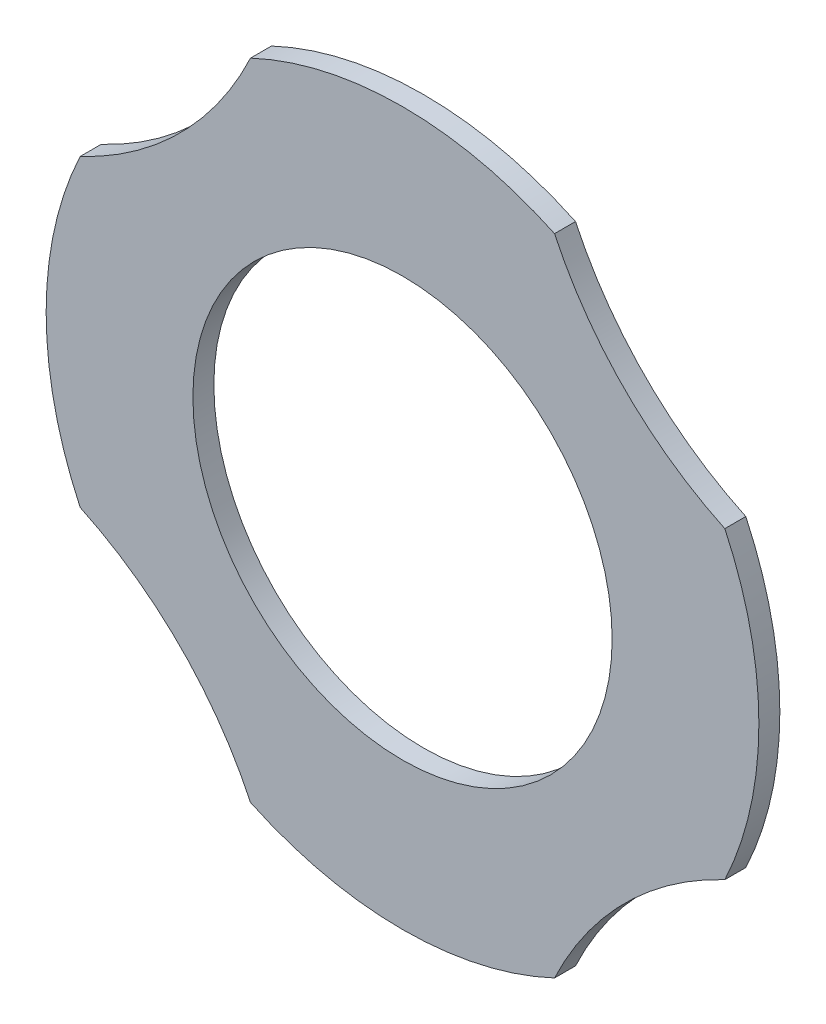
SolidWorks part; units mm, degrees
ref_plane "Alzado" through (0, 0, 0) normal (0, 0, 1) x (1, 0, 0)
ref_plane "Planta" through (0, 0, 0) normal (0, 1, 0) x (1, 0, 0)
ref_plane "Vista lateral" through (0, 0, 0) normal (1, 0, 0) x (0, 0, -1)
sketch "Croquis1" plane through (0, 0, 0) normal (0, 0, 1) x (1, 0, 0)
  line L0 (0, 320) -> (0, 650) construction
  line L1 (0, 320) -> (233.3452, 553.3452) construction
  line L2 (0, 320) -> (330, 320) construction
  line L3 (0, 320) -> (233.3452, 86.6548) construction
  line L4 (0, 320) -> (0, -10) construction
  line L5 (0, 320) -> (-233.3452, 86.6548) construction
  line L6 (0, 320) -> (-330, 320) construction
  line L7 (0, 320) -> (-233.3452, 553.3452) construction
  line L8 (0, 320) -> (0, 650) construction
  line L9 (0, 320) -> (72.5169, 473.7573) construction
  circle A0 centre (0, 0) radius 80 construction
  circle A1 centre (0, 320) radius 80 construction
  circle A2 centre (0, 320) radius 330 construction
  arc A3 (-72.5169, 473.7573) -> (72.5169, 473.7573) centre (0, 320) cw
  arc A4 (153.7573, 392.5169) -> (153.7573, 247.4831) centre (0, 320) cw
  arc A5 (72.5169, 166.2427) -> (-72.5169, 166.2427) centre (0, 320) cw
  arc A6 (-153.7573, 247.4831) -> (-153.7573, 392.5169) centre (0, 320) cw
  arc A7 (72.5169, 473.7573) -> (153.7573, 392.5169) centre (226.2742, 546.2742) ccw
  arc A8 (-153.7573, 392.5169) -> (-72.5169, 473.7573) centre (-226.2742, 546.2742) ccw
  arc A9 (-153.7573, 247.4831) -> (-72.5169, 166.2427) centre (-226.2742, 93.7258) cw
  arc A10 (72.5169, 166.2427) -> (153.7573, 247.4831) centre (226.2742, 93.7258) cw
  dimension "D1" = 160
  dimension "D3" = 660
  dimension "D7" = 170
  dimension "D2" = 320
  dimension "D5" = 4
  dimension "D6" = 170
  dimension "D8" = 320
  dimension "D4" = 8
extrude "Saliente-Extruir1" add sketch "Croquis1" along normal blind 10
sketch "Croquis2" plane through (0, 0, 10) normal (0, 0, 1) x (1, 0, 0)
  circle A0 centre (0, 320) radius 100
  dimension "D1" = 200
extrude "Cortar-Extruir1" cut sketch "Croquis2" against normal blind 10
